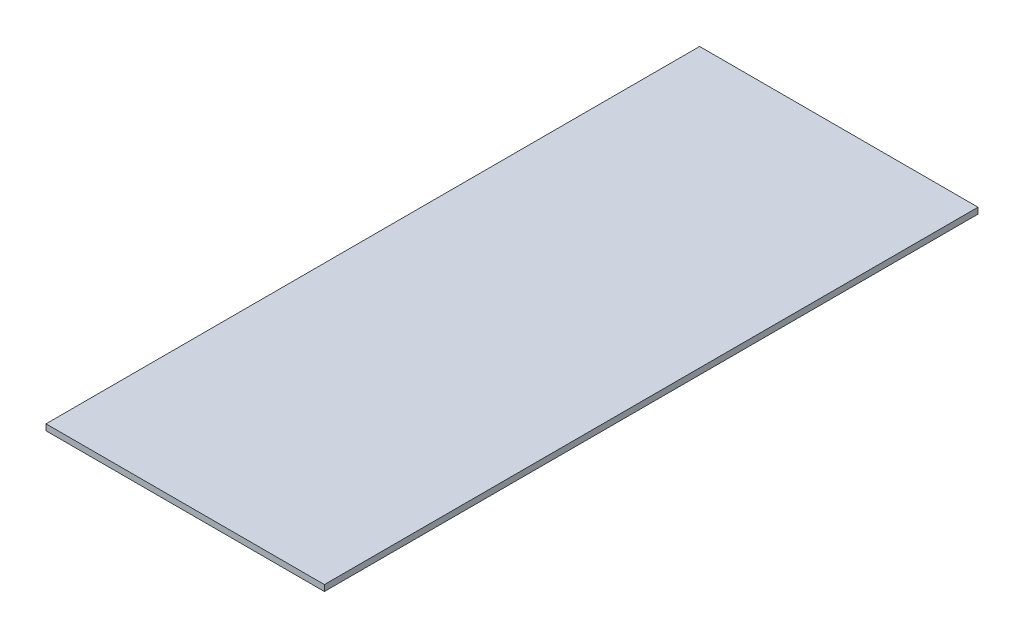
SolidWorks part; units mm, degrees
ref_plane "Front Plane" through (0, 0, 0) normal (0, 0, 1) x (1, 0, 0)
ref_plane "Top Plane" through (0, 0, 0) normal (0, 1, 0) x (1, 0, 0)
ref_plane "Right Plane" through (0, 0, 0) normal (1, 0, 0) x (0, 0, -1)
sketch "Sketch2" plane through (0, 0, 0) normal (0, 1, 0) x (1, 0, 0)
  line L1 (-146.05, -342.9) -> (146.05, -342.9)
  line L2 (-146.05, -342.9) -> (-146.05, 342.9)
  line L3 (-146.05, 342.9) -> (146.05, 342.9)
  line L4 (146.05, -342.9) -> (146.05, 342.9)
  line L5 (-146.05, -342.9) -> (146.05, 342.9) construction
  line L6 (-146.05, 342.9) -> (146.05, -342.9) construction
  point P0 (0, 0)
  dimension "D1" = 292.1
  dimension "D2" = 685.8
extrude "Boss-Extrude1" add sketch "Sketch2" along normal mid plane 6.35
